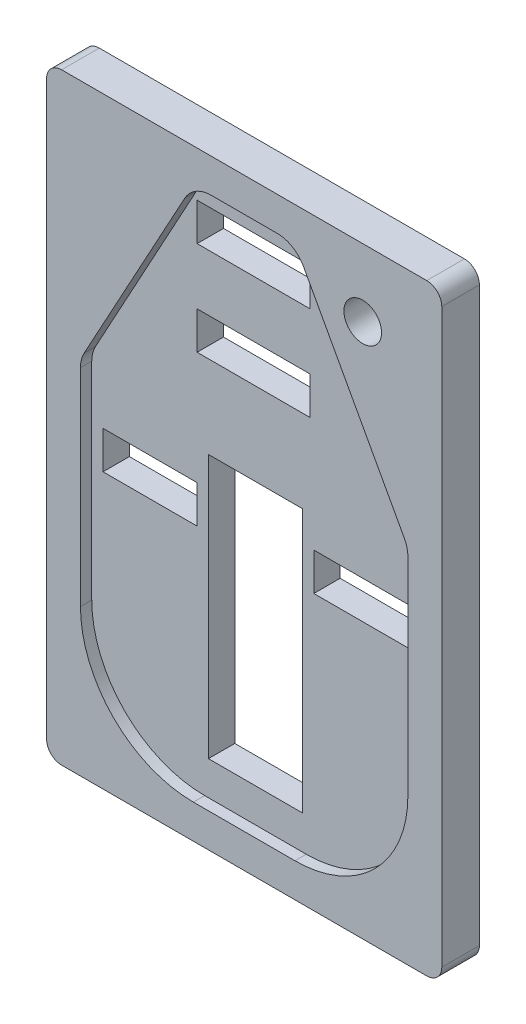
SolidWorks part; units mm, degrees
ref_plane "Front Plane" through (0, 0, 0) normal (0, 0, 1) x (1, 0, 0)
ref_plane "Top Plane" through (0, 0, 0) normal (0, 1, 0) x (1, 0, 0)
ref_plane "Right Plane" through (0, 0, 0) normal (1, 0, 0) x (0, 0, -1)
sketch "Sketch1" plane through (0, 0, 0) normal (0, 0, 1) x (1, 0, 0)
  line L1 (-49.1818, 56.9139) -> (47.8182, 56.9139)
  line L2 (-53.1818, 52.9139) -> (-53.1818, -99.0861)
  line L3 (-49.1818, -103.0861) -> (47.8182, -103.0861)
  line L4 (51.8182, 52.9139) -> (51.8182, -99.0861)
  arc A0 (-53.1818, -99.0861) -> (-49.1818, -103.0861) centre (-49.1818, -99.0861) ccw
  arc A1 (47.8182, -103.0861) -> (51.8182, -99.0861) centre (47.8182, -99.0861) ccw
  arc A2 (51.8182, 52.9139) -> (47.8182, 56.9139) centre (47.8182, 52.9139) ccw
  arc A3 (-49.1818, 56.9139) -> (-53.1818, 52.9139) centre (-49.1818, 52.9139) ccw
  point P6 (-53.1818, -103.0861)
  point P11 (51.8182, 56.9139)
  point P14 (-53.1818, 56.9139)
  dimension "D3" = 4
  dimension "D1" = 105
  dimension "D2" = 160
extrude "Boss-Extrude1" add sketch "Sketch1" along normal blind 10
sketch "Sketch3" plane through (0, 0, 10) normal (0, 0, 1) x (1, 0, 0)
  line L0 (-53.1818, 52.9139) -> (-53.1818, -99.0861) construction
  line L1 (-9.4327, 47.9139) -> (8.0691, 47.9139)
  line L2 (-44.1818, -9.1261) -> (-44.1818, -64.0861)
  line L3 (-14.1818, -94.0861) -> (12.8182, -94.0861)
  line L4 (42.8182, -9.1261) -> (42.8182, -64.0861)
  line L5 (51.8182, -99.0861) -> (51.8182, 52.9139) construction
  line L6 (-49.1818, -103.0861) -> (47.8182, -103.0861) construction
  line L7 (47.8182, 56.9139) -> (-49.1818, 56.9139) construction
  line L8 (41.8414, -5.2953) -> (15.0923, 43.7447)
  line L9 (-43.205, -5.2953) -> (-16.4559, 43.7447)
  arc A0 (-44.1818, -9.1261) -> (-43.205, -5.2953) centre (-36.1818, -9.1261) cw
  arc A1 (42.8182, -9.1261) -> (41.8414, -5.2953) centre (34.8182, -9.1261) ccw
  arc A2 (15.0923, 43.7447) -> (8.0691, 47.9139) centre (8.0691, 39.9139) ccw
  arc A3 (-9.4327, 47.9139) -> (-16.4559, 43.7447) centre (-9.4327, 39.9139) ccw
  arc A4 (42.8182, -64.0861) -> (12.8182, -94.0861) centre (12.8182, -64.0861) cw
  arc A5 (-14.1818, -94.0861) -> (-44.1818, -64.0861) centre (-14.1818, -64.0861) cw
  point P16 (-44.1818, -7.0861)
  point P19 (42.8182, -7.0861)
  point P22 (12.8182, 47.9139)
  point P25 (-14.1818, 47.9139)
  dimension "D9" = 8
  dimension "D10" = 30
  dimension "D1" = 9
  dimension "D2" = 9
  dimension "D3" = 9
  dimension "D4" = 9
  dimension "D5" = 55
  dimension "D6" = 27
  dimension "D7" = 55
  dimension "D8" = 39
extrude "Cut-Extrude1" cut sketch "Sketch3" against normal blind 3
sketch "Sketch4" plane through (0, 0, 7) normal (0, 0, 1) x (1, 0, 0)
  line L0 (51.8182, -99.0861) -> (51.8182, 52.9139) construction
  line L1 (-16.1818, 41.9139) -> (13.8182, 41.9139)
  line L2 (-16.1818, 41.9139) -> (-16.1818, 31.9139)
  line L3 (-16.1818, 31.9139) -> (13.8182, 31.9139)
  line L4 (13.8182, 41.9139) -> (13.8182, 31.9139)
  line L5 (47.8182, 56.9139) -> (-49.1818, 56.9139) construction
  line L6 (-16.1818, 16.9139) -> (13.8182, 16.9139)
  line L7 (-16.1818, 16.9139) -> (-16.1818, 6.9139)
  line L8 (-16.1818, 6.9139) -> (13.8182, 6.9139)
  line L9 (13.8182, 16.9139) -> (13.8182, 6.9139)
  line L10 (-41.1818, -23.0861) -> (-16.1818, -23.0861)
  line L11 (-41.1818, -23.0861) -> (-41.1818, -33.0861)
  line L12 (-41.1818, -33.0861) -> (-16.1818, -33.0861)
  line L13 (-16.1818, -23.0861) -> (-16.1818, -33.0861)
  line L14 (-53.1818, 52.9139) -> (-53.1818, -99.0861) construction
  line L15 (-49.1818, -103.0861) -> (47.8182, -103.0861) construction
  line L16 (14.8182, -23.0861) -> (39.8182, -23.0861)
  line L17 (14.8182, -23.0861) -> (14.8182, -33.0861)
  line L18 (14.8182, -33.0861) -> (39.8182, -33.0861)
  line L19 (39.8182, -23.0861) -> (39.8182, -33.0861)
  line L21 (-13.1818, -15.0861) -> (11.8182, -15.0861)
  line L22 (-13.1818, -15.0861) -> (-13.1818, -85.0861)
  line L23 (-13.1818, -85.0861) -> (11.8182, -85.0861)
  line L24 (11.8182, -15.0861) -> (11.8182, -85.0861)
  dimension "D1" = 30
  dimension "D2" = 10
  dimension "D3" = 38
  dimension "D4" = 15
  dimension "D5" = 38
  dimension "D6" = 40
  dimension "D10" = 10
  dimension "D11" = 30
  dimension "D12" = 10
  dimension "D13" = 25
  dimension "D14" = 12
  dimension "D15" = 70
  dimension "D16" = 10
  dimension "D17" = 25
  dimension "D18" = 12
  dimension "D19" = 70
  dimension "D20" = 18
  dimension "D21" = 25
  dimension "D22" = 70
  dimension "D23" = 40
extrude "Cut-Extrude3" cut sketch "Sketch4" against normal blind 7
sketch "Sketch5" plane through (0, 0, 10) normal (0, 0, 1) x (1, 0, 0)
  line L0 (51.8182, -99.0861) -> (51.8182, 52.9139) construction
  line L1 (47.8182, 56.9139) -> (-49.1818, 56.9139) construction
  circle A0 centre (30.8182, 38.9139) radius 5
  dimension "D1" = 10
  dimension "D2" = 21
  dimension "D3" = 18
extrude "Cut-Extrude4" cut sketch "Sketch5" against normal blind 10
